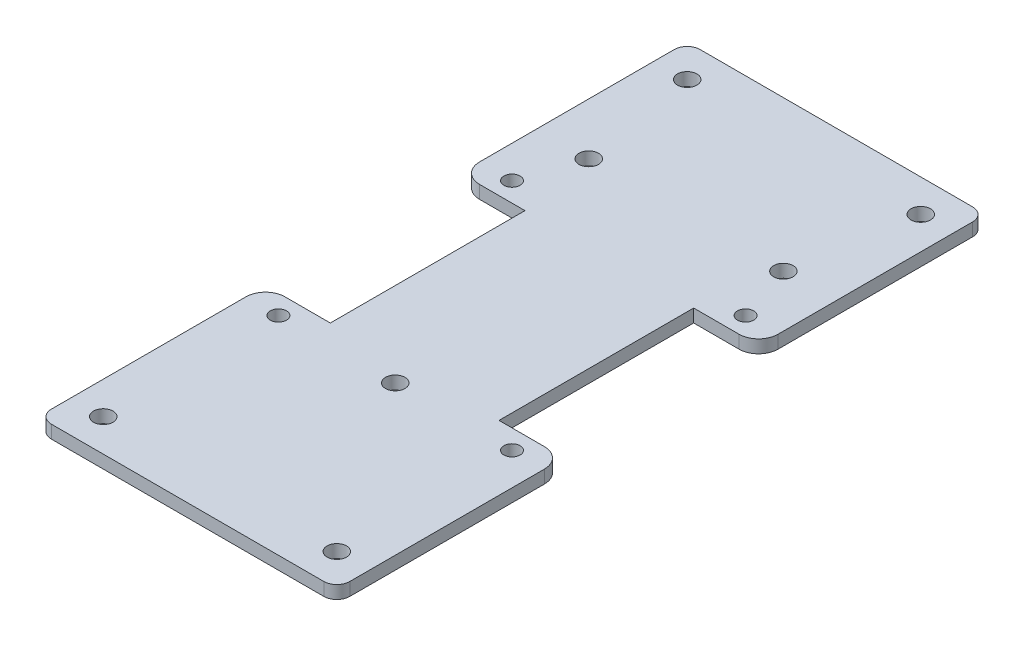
SolidWorks part; units mm, degrees
ref_plane "前视基准面" through (0, 0, 0) normal (0, 0, 1) x (1, 0, 0)
ref_plane "上视基准面" through (0, 0, 0) normal (0, 1, 0) x (1, 0, 0)
ref_plane "右视基准面" through (0, 0, 0) normal (1, 0, 0) x (0, 0, -1)
sketch "草图1" plane through (0, 0, 0) normal (0, 1, 0) x (1, 0, 0)
  line L0 (-5, 58) -> (41, 58) construction
  line L1 (0, 0) -> (36, 0) construction
  line L2 (0, 0) -> (0, 36) construction
  line L3 (0, 36) -> (36, 36) construction
  line L4 (36, 0) -> (36, 36) construction
  line L5 (-5, -32) -> (41, -32)
  line L6 (-5, -32) -> (-5, 68)
  line L7 (-5, 68) -> (41, 68)
  line L8 (41, -32) -> (41, 68)
  line L9 (0, 18) -> (36, 18) construction
  line L10 (-5, -22) -> (41, -22) construction
  line L11 (0, 63) -> (36, 63) construction
  line L12 (0, 63) -> (0, 36) construction
  line L13 (36, 63) -> (36, 36) construction
  line L14 (3, 44.83) -> (33, 44.83) construction
  line L15 (18, 36) -> (18, 0) construction
  circle A0 centre (0, 36) radius 1.25
  circle A1 centre (36, 36) radius 1.25
  circle A2 centre (0, 0) radius 1.25
  circle A3 centre (36, 0) radius 1.25
  circle A4 centre (0, 63) radius 1.5
  circle A5 centre (36, 63) radius 1.5
  circle A6 centre (36, -27) radius 1.5
  circle A7 centre (0, -27) radius 1.5
  circle A8 centre (3, 44.83) radius 1.5
  circle A9 centre (33, 44.83) radius 1.5
  circle A10 centre (18, 0) radius 1.5
  point P33 (18, 44.83)
  point P35 (0, 0.001)
  point P36 (0.001, 0.001)
  point P37 (0.001, 0)
  dimension "D3" = 2.5
  dimension "D9" = 3
  dimension "D11" = 30
  dimension "D12" = 3
  dimension "D13" = 44.83
  dimension "D1" = 36
  dimension "D2" = 36
  dimension "D4" = 80
  dimension "D5" = 5
  dimension "D6" = 5
  dimension "D7" = 10
  dimension "D8" = 10
  dimension "D10" = 5
extrude "凸台-拉伸1" add sketch "草图1" along normal blind 2
ref_plane "基准面1" through (0, 0, 0) normal (0, -1, 0) x (-1, 0, 0)
fillet "圆角1" radius 2 4 edges at (-5, 1, 32) (41, 1, 32) (-5, 1, -68) (41, 1, -68)
sketch "草图2" plane through (0, 2, 0) normal (0, 1, 0) x (1, 0, 0)
  line L0 (-5, 33) -> (5, 33)
  line L1 (-5, 66) -> (-5, -30) construction
  line L2 (5, 33) -> (5, 3)
  line L3 (5, 3) -> (-5, 3)
  line L4 (-5, 3) -> (-5, 33)
  line L5 (18, 68) -> (18, -32) construction
  line L6 (39, 68) -> (-3, 68) construction
  line L7 (-3, -32) -> (39, -32) construction
  line L8 (31, 3) -> (41, 3)
  line L9 (31, 33) -> (31, 3)
  line L10 (41, 33) -> (31, 33)
  line L11 (41, 3) -> (41, 33)
  circle A0 centre (0, 36) radius 1.25 construction
  dimension "D1" = 3
  dimension "D2" = 10
  dimension "D3" = 3
extrude "切除-拉伸1" cut sketch "草图2" against normal through all
fillet "圆角2" radius 3 4 edges at (41, 1, -33) (41, 1, -3) (-5, 1, -3) (-5, 1, -33)
